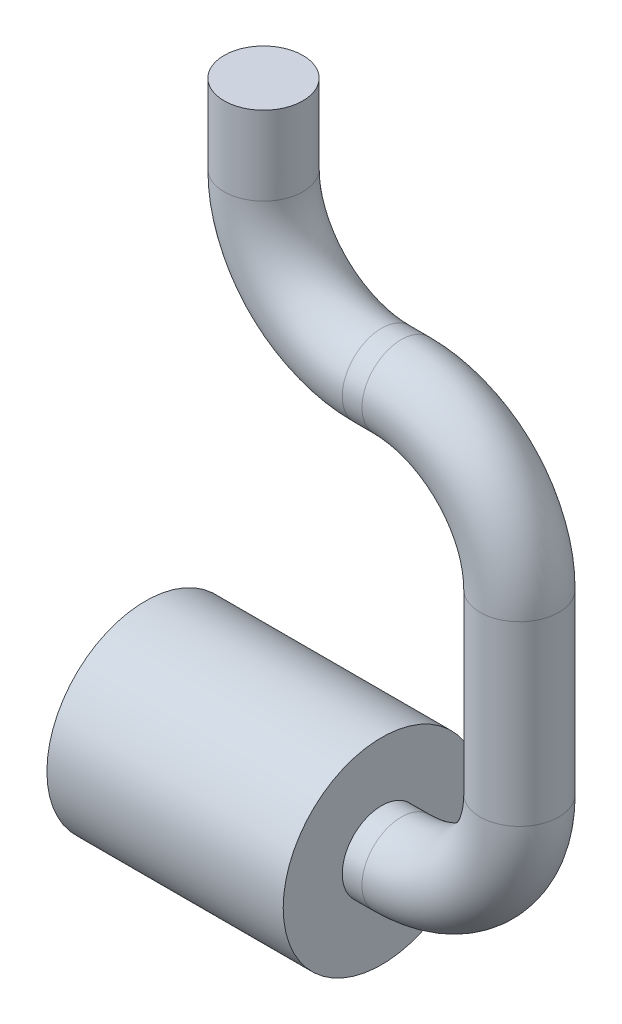
SolidWorks part; units mm, degrees
material "1060 Alloy"
ref_plane "Front Plane" through (0, 0, 0) normal (0, 0, 1) x (1, 0, 0)
ref_plane "Top Plane" through (0, 0, 0) normal (0, 1, 0) x (1, 0, 0)
ref_plane "Right Plane" through (0, 0, 0) normal (1, 0, 0) x (0, 0, -1)
sketch "Sketch1" plane through (0, 0, 0) normal (1, 0, 0) x (0, 0, -1)
  circle A0 centre (0, 0) radius 12.5
  dimension "D1" = 25
extrude "Boss-Extrude1" add sketch "Sketch1" along normal mid plane 30
sketch "Sketch7" plane through (0, 0, 0) normal (0, 0, 1) x (1, 0, 0)
  line L0 (15, 0) -> (17.5, 0)
  line L1 (15, -12.5) -> (15, 12.5) construction
  line L2 (13.75, 0) -> (-13.75, 0) construction
  line L3 (32.5, 15) -> (32.5, 37.5)
  line L4 (17.5, 52.5) -> (15, 52.5)
  line L5 (0, 67.5) -> (0, 77.5)
  line L6 (0, -13.75) -> (0, 13.75) construction
  arc A0 (0, 67.5) -> (15, 52.5) centre (15, 67.5) ccw
  arc A1 (17.5, 52.5) -> (32.5, 37.5) centre (17.5, 37.5) cw
  arc A2 (32.5, 15) -> (17.5, 0) centre (17.5, 15) cw
  point P14 (0, 52.5)
  point P17 (32.5, 52.5)
  point P20 (32.5, 0)
  dimension "D4" = 15
  dimension "D1" = 32.5
  dimension "D2" = 52.5
  dimension "D3" = 25
sketch "Sketch8" plane through (15, 0, 0) normal (1, 0, 0) x (0, 0, -1)
  circle A0 centre (0, 0) radius 5
  dimension "D1" = 10
sweep "Sweep1" add profiles "Sketch8" path "Sketch7"
